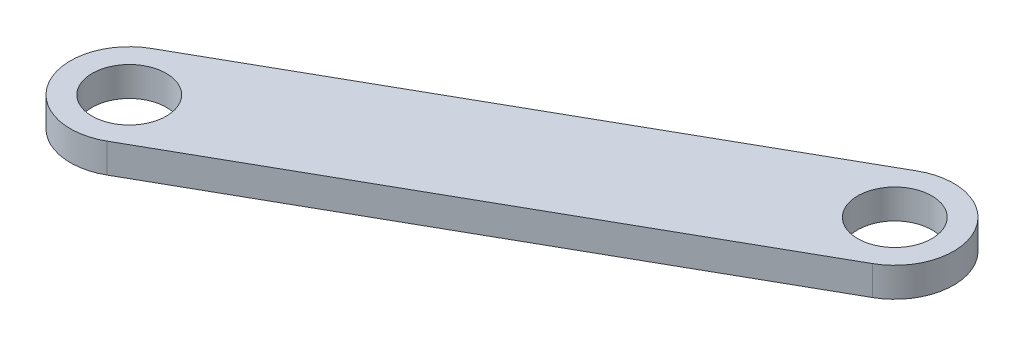
SolidWorks part; units mm, degrees
material "5052-H32"
ref_plane "X-Y Datum" through (0, 0, 0) normal (0, 0, 1) x (1, 0, 0)
ref_plane "X-Z Datum" through (0, 0, 0) normal (0, 1, 0) x (1, 0, 0)
ref_plane "Y-Z Datum" through (0, 0, 0) normal (1, 0, 0) x (0, 0, -1)
sketch "Sketch1" plane through (0, 0, 0) normal (0, 1, 0) x (1, 0, 0)
  line L0 (1.564, -2.7631) -> (-24.7986, -17.6856)
  line L1 (-1.564, 2.7631) -> (-27.9266, -12.1594)
  line L2 (0, 0) -> (-26.3626, -14.9225) construction
  circle A0 centre (0, 0) radius 2
  circle A1 centre (-26.3626, -14.9225) radius 2
  arc A2 (-24.7986, -17.6856) -> (-27.9266, -12.1594) centre (-26.3626, -14.9225) cw
  arc A3 (-1.564, 2.7631) -> (1.564, -2.7631) centre (0, 0) cw
  dimension "D1" = 4
  dimension "D2" = 14.9225
  dimension "D5" = 3.175
  dimension "D3" = 26.3626
extrude "Boss-Extrude1" add sketch "Sketch1" against normal blind 1.5875
